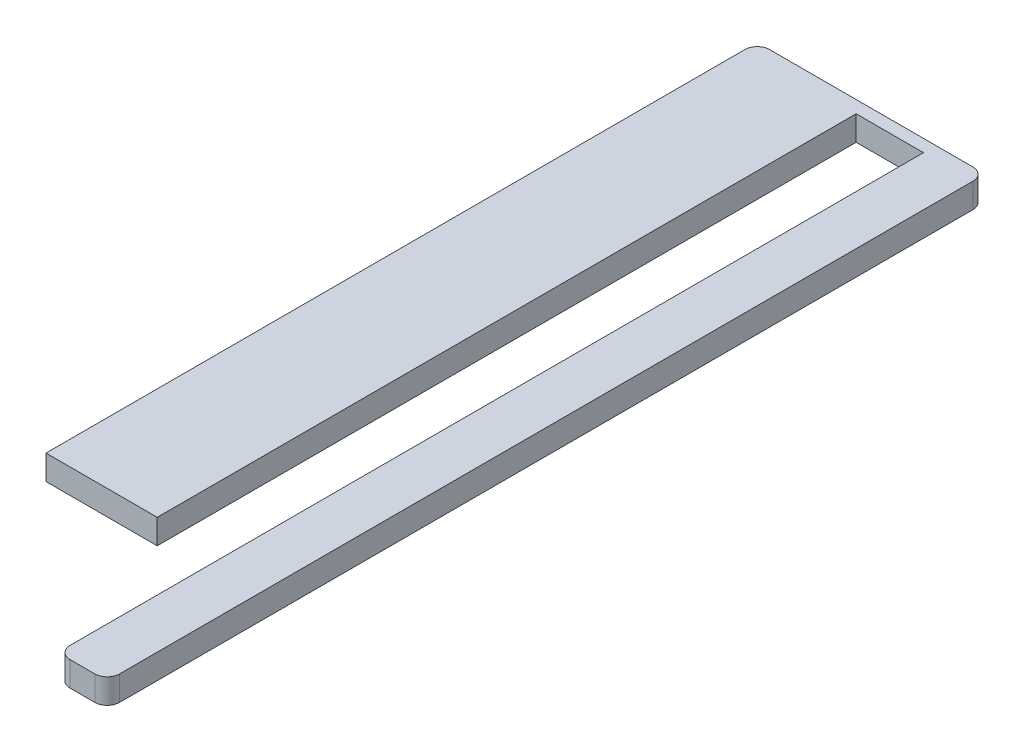
SolidWorks part; units mm, degrees
ref_plane "正面" through (0, 0, 0) normal (0, 0, 1) x (1, 0, 0)
ref_plane "平面" through (0, 0, 0) normal (0, 1, 0) x (1, 0, 0)
ref_plane "右側面" through (0, 0, 0) normal (1, 0, 0) x (0, 0, -1)
sketch "ｽｹｯﾁ2" plane through (0, 0, 0) normal (0, 1, 0) x (1, 0, 0)
  line L0 (0, 0) -> (9, 0)
  line L1 (9, 0) -> (9, 56.55)
  line L2 (9, 56.55) -> (14.45, 56.55)
  line L3 (14.45, 56.55) -> (14.45, -12.5)
  line L4 (15.45, -13.5) -> (17.45, -13.5)
  line L5 (18.45, -12.5) -> (18.45, 56.55)
  line L6 (17.45, 57.55) -> (1, 57.55)
  line L7 (0, 56.55) -> (0, 0)
  arc A0 (1, 57.55) -> (0, 56.55) centre (1, 56.55) ccw
  arc A1 (18.45, 56.55) -> (17.45, 57.55) centre (17.45, 56.55) ccw
  arc A2 (17.45, -13.5) -> (18.45, -12.5) centre (17.45, -12.5) ccw
  arc A3 (14.45, -12.5) -> (15.45, -13.5) centre (15.45, -12.5) ccw
  point P11 (0, 57.55)
  point P14 (18.45, 57.55)
  point P17 (18.45, -13.5)
  point P20 (14.45, -13.5)
  dimension "D5" = 1
  dimension "D8" = 1
  dimension "D1" = 57.55
  dimension "D2" = 18.45
  dimension "D3" = 71.05
  dimension "D4" = 1
  dimension "D6" = 4
  dimension "D7" = 9
extrude "ﾎﾞｽ - 押し出し1" add sketch "ｽｹｯﾁ2" along normal blind 2
